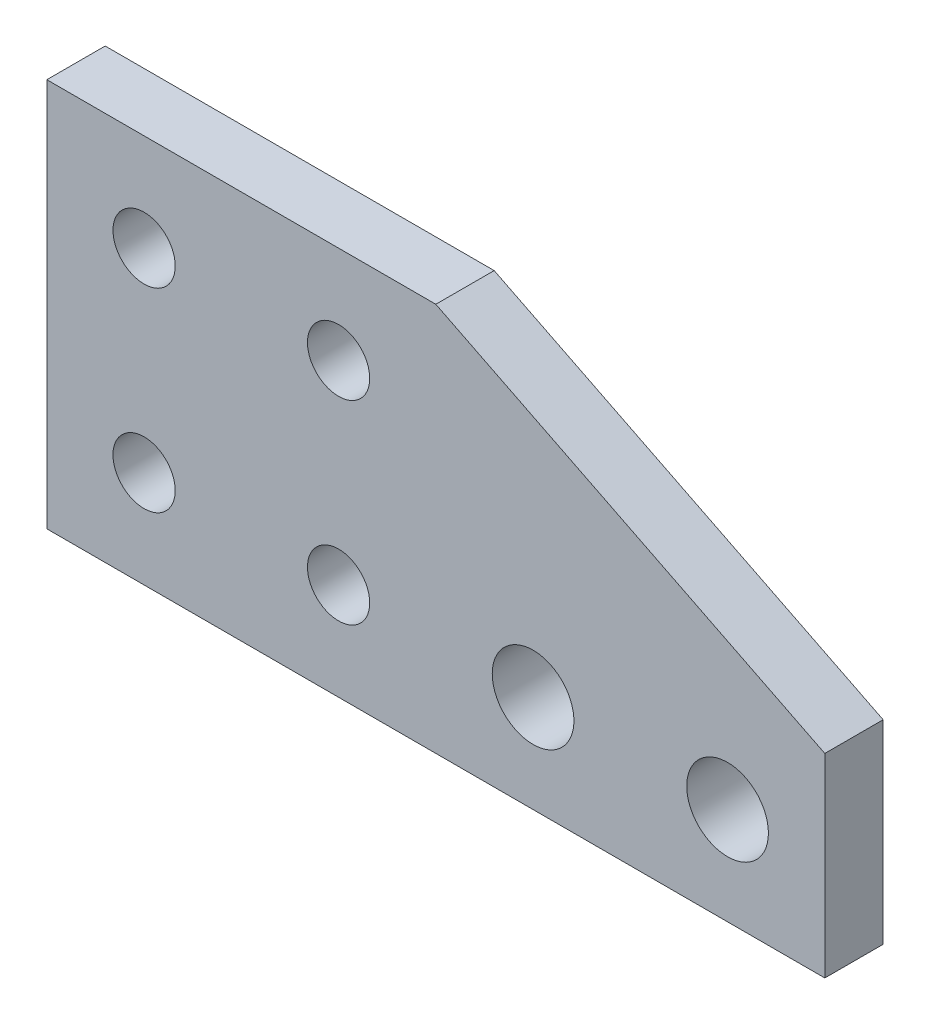
SolidWorks part; units mm, degrees
ref_plane "前视基准面" through (0, 0, 0) normal (0, 0, 1) x (1, 0, 0)
ref_plane "上视基准面" through (0, 0, 0) normal (0, 1, 0) x (1, 0, 0)
ref_plane "右视基准面" through (0, 0, 0) normal (1, 0, 0) x (0, 0, -1)
other "Configuration Table"
sketch "草图1" plane through (0, 0, 0) normal (0, 0, 1) x (1, 0, 0)
  line L0 (0, 0) -> (20, 0)
  line L1 (20, 0) -> (20, -10)
  line L2 (20, -10) -> (40, -10)
  line L3 (40, -10) -> (40, -20)
  line L4 (40, -20) -> (0, -20)
  line L5 (0, -20) -> (0, 0)
  dimension "D1" = 20
  dimension "D2" = 10
  dimension "D3" = 10
  dimension "D4" = 20
extrude "凸台-拉伸1" add sketch "草图1" along normal blind 3
sketch "草图2" plane through (0, 0, 3) normal (0, 0, 1) x (1, 0, 0)
  line L0 (20, -10) -> (0, -10) construction
  line L3 (10, 0) -> (10, -10) construction
  line L4 (20, 0) -> (0, 0) construction
  line L5 (30, -10) -> (30, -20) construction
  line L6 (40, -10) -> (20, -10) construction
  line L7 (0, -20) -> (40, -20) construction
  line L8 (40, -15) -> (30, -15) construction
  line L9 (40, -20) -> (40, -10) construction
  circle A0 centre (5, -5) radius 1.6
  circle A2 centre (5, -15) radius 1.6
  circle A3 centre (15, -5) radius 1.6
  circle A4 centre (15, -15) radius 1.6
  circle A5 centre (35, -15) radius 2.1
  circle A6 centre (25, -15) radius 2.1
  dimension "D1" = 3.2
  dimension "D4" = 4.2
  dimension "D2" = 5
  dimension "D3" = 5
  dimension "D5" = 5
  dimension "D7" = 10
extrude "切除-拉伸1" cut sketch "草图2" against normal through all
sketch "草图4" plane through (0, 0, 3) normal (0, 0, 1) x (1, 0, 0)
  line L0 (20, 0) -> (40, -10)
  line L1 (40, -10) -> (20, -10)
  line L2 (20, -10) -> (20, 0)
extrude "凸台-拉伸2" add sketch "草图4" against normal blind 3
